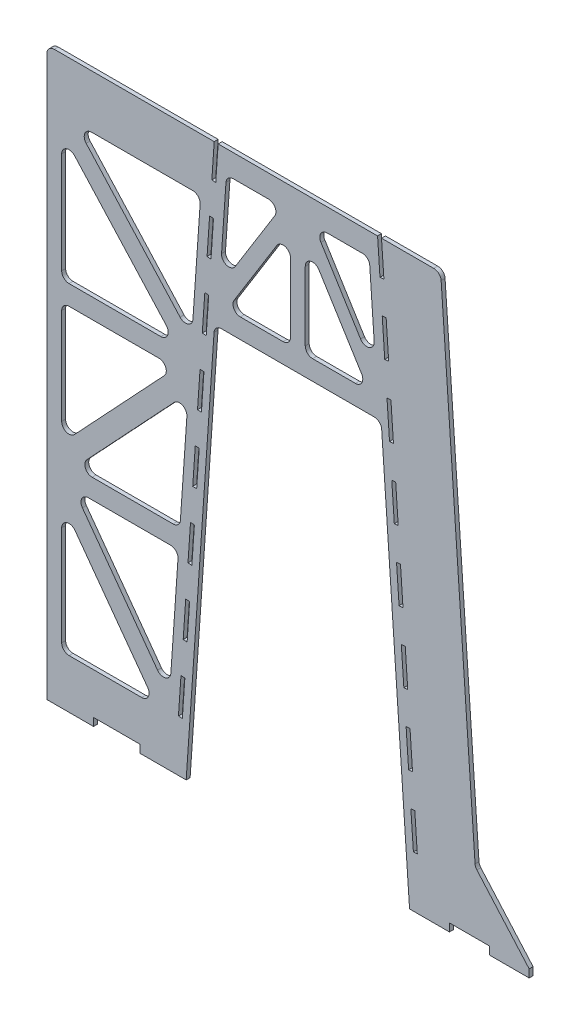
SolidWorks part; units mm, degrees
material "A-Glass Fiber"
ref_plane "Front Plane" through (0, 0, 0) normal (0, 0, 1) x (1, 0, 0)
ref_plane "Top Plane" through (0, 0, 0) normal (0, 1, 0) x (1, 0, 0)
ref_plane "Right Plane" through (0, 0, 0) normal (1, 0, 0) x (0, 0, -1)
sketch "Sketch1" plane through (0, 0, 0) normal (0, 0, 1) x (1, 0, 0)
  line L0 (-288.2759, 0) -> (288.2759, 0) construction
  line L1 (-215.8925, 1463.04) -> (215.8925, 1463.04)
  line L2 (0, 0) -> (0, 1733.4513) construction
  line L3 (19.05, 1104.9) -> (205.1391, 1104.9)
  line L4 (202.3135, 1145.5664) -> (41.4731, 1404.62)
  line L5 (205.1391, 1104.9) -> (19.05, 1404.62) construction
  line L6 (205.1391, 1104.9) -> (184.3133, 1404.62)
  line L7 (182.716, 1104.9) -> (19.05, 1368.5047)
  line L8 (19.05, 1404.62) -> (19.05, 1104.9)
  line L9 (184.3133, 1404.62) -> (19.05, 1404.62)
  line L10 (205.7153, 1463.04) -> (307.3735, 0)
  line L11 (317.5154, 0.5076) -> (215.8925, 1463.04)
  line L12 (317.5154, 0.5076) -> (317.5507, 0)
  line L13 (288.2759, 0) -> (215.0326, 1054.1)
  line L14 (447.7407, 0) -> (391.1675, 0) construction
  line L15 (266.6925, 1463.04) -> (368.5375, 1463.04)
  line L16 (368.5375, 1463.04) -> (457.7693, 178.8376)
  line L81 (215.8925, 1463.04) -> (266.6925, 1463.04)
  line L82 (-215.8925, 1463.04) -> (-647.7182, 1463.04)
  line L88 (317.5507, 0) -> (307.3718, 0)
  line L90 (215.0326, 1054.1) -> (-215.0326, 1054.1)
  line L92 (307.3718, 0) -> (288.2759, 0)
  line L93 (-288.2759, 0) -> (-215.0326, 1054.1)
  line L94 (-307.3735, 0) -> (-288.2759, 0)
  line L97 (-317.5507, 0) -> (-307.3735, 0)
  line L98 (-317.5154, 0.5076) -> (-317.5507, 0)
  line L99 (-317.5154, 0.5076) -> (-215.8925, 1463.04)
  line L100 (-205.7153, 1463.04) -> (-307.3735, 0)
  line L124 (-184.3133, 1404.62) -> (-19.05, 1404.62)
  line L125 (-19.05, 1404.62) -> (-19.05, 1104.9)
  line L126 (-182.716, 1104.9) -> (-19.05, 1368.5047)
  line L127 (-205.1391, 1104.9) -> (-19.05, 1404.62) construction
  line L128 (-202.3135, 1145.5664) -> (-41.4731, 1404.62)
  line L129 (-205.1391, 1104.9) -> (-184.3133, 1404.62)
  line L130 (-19.05, 1104.9) -> (-205.1391, 1104.9)
  line L131 (-317.5507, 0) -> (-647.7182, 0)
  line L132 (-647.7182, 0) -> (-647.7182, 1463.04)
  line L133 (-647.7182, 0) -> (-317.5507, 0)
  line L134 (-308.7262, 127) -> (-647.7182, 127)
  line L135 (-647.7182, 1325.88) -> (-225.423, 1325.88)
  line L136 (317.5507, 0) -> (368.3507, 0)
  line L137 (368.3507, 0) -> (266.6925, 1463.04)
  line L138 (368.3507, 0) -> (317.5507, 0)
  line L139 (-250.8842, 1325.88) -> (-334.1875, 127)
  line L140 (-609.6182, 127) -> (-609.6182, 1325.88)
  line L141 (-306.1844, 530.0133) -> (-609.6182, 530.0133)
  line L142 (-278.1813, 933.0267) -> (-609.6182, 933.0267)
  line L143 (-304.4195, 555.4133) -> (-609.6182, 555.4133)
  line L144 (-307.9493, 504.6133) -> (-609.6182, 504.6133)
  line L145 (-279.9462, 907.6267) -> (-609.6182, 907.6267)
  line L146 (-276.4164, 958.4267) -> (-609.6182, 958.4267)
  line L147 (-334.1875, 127) -> (-609.6182, 504.6133) construction
  line L148 (-609.6182, 555.4133) -> (-279.9462, 907.6267) construction
  line L149 (-276.4164, 958.4267) -> (-609.6182, 1325.88) construction
  line L150 (-331.453, 166.3535) -> (-578.1794, 504.6133)
  line L151 (-574.8276, 555.4133) -> (-282.736, 867.4768)
  line L152 (-273.976, 993.5478) -> (-575.3304, 1325.88)
  line L153 (-365.6263, 127) -> (-609.6182, 461.511)
  line L154 (-609.6182, 592.5827) -> (-314.7368, 907.6267)
  line L155 (-310.7042, 958.4267) -> (-609.6182, 1288.0676)
  line L156 (368.3507, 0) -> (596.9507, 0)
  line L157 (596.9507, 0) -> (596.9507, 20.32)
  line L158 (596.9507, 20.32) -> (347.1719, 304.8)
  point P0 (0, 0)
  point P3 (0, 0)
  point P106 (0, 0)
  point P118 (0, 1054.1)
  dimension "D6" = 25.4
  dimension "D7" = 50.8
  dimension "D8" = 58.42
  dimension "D9" = 19.05
  dimension "D10" = 647.7182
  dimension "D11" = 10.1527
  dimension "D12" = 25.4
  dimension "D13" = 25.4
  dimension "D14" = 25.4
  dimension "D15" = 25.4
  dimension "D16" = 25.4
  dimension "D17" = 25.4
  dimension "D18" = 1463.04
  dimension "D19" = 288.2759
  dimension "D20" = 29.2044
  dimension "D21" = 101.6
  dimension "D22" = 19.05
  dimension "D23" = 19.05
  dimension "D24" = 1054.1
  dimension "D25" = 20.32
  dimension "D37" = 127
  dimension "D38" = 50.8
  dimension "D39" = 25.4
  dimension "D40" = 38.1
  dimension "D41" = 403.0133
  dimension "D42" = 403.0133
  dimension "D43" = 25.4
  dimension "D44" = 25.4
  dimension "D45" = 25.4
  dimension "D46" = 25.4
  dimension "D47" = 279.4
  dimension "D48" = 304.8
  dimension "D49" = 50.8
  dimension "D52" = 137.16
extrude "Boss-Extrude1" add sketch "Sketch1" along normal blind 10.16
fillet "Fillet1" radius 19.05 35 edges at (-215.0326, 1054.1, 5.08) (215.0326, 1054.1, 5.08) (-202.3135, 1145.5664, 5.08) (-19.05, 1104.9, 5.08) (-182.716, 1104.9, 5.08) (-19.05, 1368.5047, 5.08) (-41.4731, 1404.62, 5.08) (-184.3133, 1404.62, 5.08) (-647.7182, 1463.04, 5.08) (-250.8842, 1325.88, 5.08) (-575.3304, 1325.88, 5.08) (-273.976, 993.5478, 5.08) (-609.6182, 958.4267, 5.08) (-609.6182, 1288.0676, 5.08) (-310.7042, 958.4267, 5.08) (-609.6182, 592.5827, 5.08) (-314.7368, 907.6267, 5.08) (-609.6182, 907.6267, 5.08) (-574.8276, 555.4133, 5.08) (-304.4195, 555.4133, 5.08) (-282.736, 867.4768, 5.08) (-307.9493, 504.6133, 5.08) (-331.453, 166.3535, 5.08) (-578.1794, 504.6133, 5.08) (-609.6182, 461.511, 5.08) (-365.6263, 127, 5.08) (-609.6182, 127, 5.08) (19.05, 1104.9, 5.08) (184.3133, 1404.62, 5.08) (41.4731, 1404.62, 5.08) (182.716, 1104.9, 5.08) (19.05, 1368.5047, 5.08) (202.3135, 1145.5664, 5.08) (457.7693, 178.8376, 5.08) (368.5375, 1463.04, 5.08)
sketch "Sketch2" plane through (0, 0, 10.16) normal (0, 0, 1) x (1, 0, 0)
  line L28 (215.8818, 1463.04) -> (205.7153, 1463.04) construction
  line L29 (205.7153, 1463.04) -> (211.9231, 1373.6642) construction
  line L30 (211.9231, 1373.6642) -> (222.0407, 1374.3669) construction
  line L31 (222.0407, 1374.3669) -> (215.8818, 1463.04) construction
  line L32 (217.7192, 1290.2141) -> (224.241, 1196.3181) construction
  line L33 (224.241, 1196.3181) -> (234.3587, 1197.0208) construction
  line L34 (234.3587, 1197.0208) -> (227.8369, 1290.9169) construction
  line L35 (227.8369, 1290.9169) -> (217.7192, 1290.2141) construction
  line L64 (230.039, 1112.8414) -> (236.5589, 1018.9719) construction
  line L65 (236.5589, 1018.9719) -> (246.6766, 1019.6747) construction
  line L66 (246.6766, 1019.6747) -> (240.1567, 1113.5442) construction
  line L67 (240.1567, 1113.5442) -> (230.039, 1112.8414) construction
  line L68 (242.3588, 935.4688) -> (248.8768, 841.6258) construction
  line L69 (248.8768, 841.6258) -> (258.9945, 842.3285) construction
  line L70 (258.9945, 842.3285) -> (252.4764, 936.1715) construction
  line L71 (252.4764, 936.1715) -> (242.3588, 935.4688) construction
  line L72 (254.6785, 758.0961) -> (261.1947, 664.2796) construction
  line L73 (261.1947, 664.2796) -> (271.3124, 664.9824) construction
  line L74 (271.3124, 664.9824) -> (264.7962, 758.7989) construction
  line L75 (264.7962, 758.7989) -> (254.6785, 758.0961) construction
  line L76 (266.9983, 580.7234) -> (273.5126, 486.9335) construction
  line L77 (273.5126, 486.9335) -> (283.6303, 487.6362) construction
  line L78 (283.6303, 487.6362) -> (277.1159, 581.4262) construction
  line L79 (277.1159, 581.4262) -> (266.9983, 580.7234) construction
  line L80 (279.318, 403.3508) -> (285.8305, 309.5874) construction
  line L81 (285.8305, 309.5874) -> (295.9482, 310.2901) construction
  line L82 (295.9482, 310.2901) -> (289.4357, 404.0535) construction
  line L83 (289.4357, 404.0535) -> (279.318, 403.3508) construction
  line L84 (291.6378, 225.9781) -> (298.1484, 132.2412) construction
  line L85 (298.1484, 132.2412) -> (308.2661, 132.944) construction
  line L86 (308.2661, 132.944) -> (301.7555, 226.6808) construction
  line L87 (301.7555, 226.6808) -> (291.6378, 225.9781) construction
  line L116 (215.8818, 1463.04) -> (205.7153, 1463.04)
  line L117 (205.7153, 1463.04) -> (211.9231, 1373.6642)
  line L118 (211.9231, 1373.6642) -> (222.0407, 1374.3669)
  line L119 (222.0407, 1374.3669) -> (215.8818, 1463.04)
  line L120 (217.7192, 1290.2141) -> (224.241, 1196.3181)
  line L121 (224.241, 1196.3181) -> (234.3587, 1197.0208)
  line L122 (234.3587, 1197.0208) -> (227.8369, 1290.9169)
  line L123 (227.8369, 1290.9169) -> (217.7192, 1290.2141)
  line L152 (230.039, 1112.8414) -> (236.5589, 1018.9719)
  line L153 (236.5589, 1018.9719) -> (246.6766, 1019.6747)
  line L154 (246.6766, 1019.6747) -> (240.1567, 1113.5442)
  line L155 (240.1567, 1113.5442) -> (230.039, 1112.8414)
  line L156 (242.3588, 935.4688) -> (248.8768, 841.6258)
  line L157 (248.8768, 841.6258) -> (258.9945, 842.3285)
  line L158 (258.9945, 842.3285) -> (252.4764, 936.1715)
  line L159 (252.4764, 936.1715) -> (242.3588, 935.4688)
  line L160 (254.6785, 758.0961) -> (261.1947, 664.2796)
  line L161 (261.1947, 664.2796) -> (271.3124, 664.9824)
  line L162 (271.3124, 664.9824) -> (264.7962, 758.7989)
  line L163 (264.7962, 758.7989) -> (254.6785, 758.0961)
  line L164 (266.9983, 580.7234) -> (273.5126, 486.9335)
  line L165 (273.5126, 486.9335) -> (283.6303, 487.6362)
  line L166 (283.6303, 487.6362) -> (277.1159, 581.4262)
  line L167 (277.1159, 581.4262) -> (266.9983, 580.7234)
  line L168 (279.318, 403.3508) -> (285.8305, 309.5874)
  line L169 (285.8305, 309.5874) -> (295.9482, 310.2901)
  line L170 (295.9482, 310.2901) -> (289.4357, 404.0535)
  line L171 (289.4357, 404.0535) -> (279.318, 403.3508)
  line L172 (291.6378, 225.9781) -> (298.1484, 132.2412)
  line L173 (298.1484, 132.2412) -> (308.2661, 132.944)
  line L174 (308.2661, 132.944) -> (301.7555, 226.6808)
  line L175 (301.7555, 226.6808) -> (291.6378, 225.9781)
  line L194 (-134.539, 20.32) -> (-288.2759, 20.32) construction
  line L195 (-647.7182, 0) -> (-527.4335, 0)
  line L196 (-647.7182, 0) -> (-647.7182, 20.32)
  line L197 (-647.7182, 20.32) -> (-527.4335, 20.32)
  line L198 (-527.4335, 0) -> (-527.4335, 20.32)
  line L199 (-288.2759, 0) -> (-216.2645, 1036.3705) construction
  line L200 (-527.4335, 0) -> (-407.1487, 0)
  line L201 (-527.4335, 0) -> (-527.4335, 20.32)
  line L202 (-527.4335, 20.32) -> (-407.1487, 20.32)
  line L203 (-407.1487, 0) -> (-407.1487, 20.32)
  line L204 (-407.1487, 0) -> (-286.864, 0)
  line L205 (-407.1487, 0) -> (-407.1487, 20.32)
  line L206 (-407.1487, 20.32) -> (-286.864, 20.32)
  line L207 (-286.864, 0) -> (-286.864, 20.32)
  line L213 (288.2759, 20.32) -> (134.539, 20.32) construction
  line L230 (288.2759, 0) -> (391.1675, 0)
  line L231 (288.2759, 0) -> (288.2759, 20.32)
  line L232 (288.2759, 20.32) -> (391.1675, 20.32)
  line L233 (391.1675, 0) -> (391.1675, 20.32)
  line L235 (391.1675, 0) -> (494.0591, 0)
  line L236 (391.1675, 0) -> (391.1675, 20.32)
  line L237 (391.1675, 20.32) -> (494.0591, 20.32)
  line L238 (494.0591, 0) -> (494.0591, 20.32)
  line L239 (494.0591, 0) -> (596.9507, 0)
  line L240 (494.0591, 0) -> (494.0591, 20.32)
  line L241 (494.0591, 20.32) -> (596.9507, 20.32)
  line L242 (596.9507, 0) -> (596.9507, 20.32)
  line L254 (-205.7153, 1463.04) -> (-215.8818, 1463.04) construction
  line L255 (-215.8818, 1463.04) -> (-222.0407, 1374.3669) construction
  line L256 (-222.0407, 1374.3669) -> (-211.9231, 1373.6642) construction
  line L257 (-211.9231, 1373.6642) -> (-205.7153, 1463.04) construction
  line L258 (-224.241, 1196.3181) -> (-217.7192, 1290.2141) construction
  line L259 (-217.7192, 1290.2141) -> (-227.8369, 1290.9169) construction
  line L260 (-227.8369, 1290.9169) -> (-234.3587, 1197.0208) construction
  line L261 (-234.3587, 1197.0208) -> (-224.241, 1196.3181) construction
  line L262 (-236.5589, 1018.9719) -> (-230.039, 1112.8414) construction
  line L263 (-230.039, 1112.8414) -> (-240.1567, 1113.5442) construction
  line L264 (-240.1567, 1113.5442) -> (-246.6766, 1019.6747) construction
  line L265 (-246.6766, 1019.6747) -> (-236.5589, 1018.9719) construction
  line L266 (-248.8768, 841.6258) -> (-242.3588, 935.4688) construction
  line L267 (-242.3588, 935.4688) -> (-252.4764, 936.1715) construction
  line L268 (-252.4764, 936.1715) -> (-258.9945, 842.3285) construction
  line L269 (-258.9945, 842.3285) -> (-248.8768, 841.6258) construction
  line L270 (-261.1947, 664.2796) -> (-254.6785, 758.0961) construction
  line L271 (-254.6785, 758.0961) -> (-264.7962, 758.7989) construction
  line L272 (-264.7962, 758.7989) -> (-271.3124, 664.9824) construction
  line L273 (-271.3124, 664.9824) -> (-261.1947, 664.2796) construction
  line L274 (-273.5126, 486.9335) -> (-266.9983, 580.7234) construction
  line L275 (-266.9983, 580.7234) -> (-277.1159, 581.4262) construction
  line L276 (-277.1159, 581.4262) -> (-283.6303, 487.6362) construction
  line L277 (-283.6303, 487.6362) -> (-273.5126, 486.9335) construction
  line L278 (-285.8305, 309.5874) -> (-279.318, 403.3508) construction
  line L279 (-279.318, 403.3508) -> (-289.4357, 404.0535) construction
  line L280 (-289.4357, 404.0535) -> (-295.9482, 310.2901) construction
  line L281 (-295.9482, 310.2901) -> (-285.8305, 309.5874) construction
  line L282 (-298.1484, 132.2412) -> (-291.6378, 225.9781) construction
  line L283 (-291.6378, 225.9781) -> (-301.7555, 226.6808) construction
  line L284 (-301.7555, 226.6808) -> (-308.2661, 132.944) construction
  line L285 (-308.2661, 132.944) -> (-298.1484, 132.2412) construction
  line L298 (-205.7153, 1463.04) -> (-215.8818, 1463.04)
  line L299 (-215.8818, 1463.04) -> (-222.0407, 1374.3669)
  line L300 (-222.0407, 1374.3669) -> (-211.9231, 1373.6642)
  line L301 (-211.9231, 1373.6642) -> (-205.7153, 1463.04)
  line L302 (-224.241, 1196.3181) -> (-217.7192, 1290.2141)
  line L303 (-217.7192, 1290.2141) -> (-227.8369, 1290.9169)
  line L304 (-227.8369, 1290.9169) -> (-234.3587, 1197.0208)
  line L305 (-234.3587, 1197.0208) -> (-224.241, 1196.3181)
  line L306 (-236.5589, 1018.9719) -> (-230.039, 1112.8414)
  line L307 (-230.039, 1112.8414) -> (-240.1567, 1113.5442)
  line L308 (-240.1567, 1113.5442) -> (-246.6766, 1019.6747)
  line L309 (-246.6766, 1019.6747) -> (-236.5589, 1018.9719)
  line L310 (-248.8768, 841.6258) -> (-242.3588, 935.4688)
  line L311 (-242.3588, 935.4688) -> (-252.4764, 936.1715)
  line L312 (-252.4764, 936.1715) -> (-258.9945, 842.3285)
  line L313 (-258.9945, 842.3285) -> (-248.8768, 841.6258)
  line L314 (-261.1947, 664.2796) -> (-254.6785, 758.0961)
  line L315 (-254.6785, 758.0961) -> (-264.7962, 758.7989)
  line L316 (-264.7962, 758.7989) -> (-271.3124, 664.9824)
  line L317 (-271.3124, 664.9824) -> (-261.1947, 664.2796)
  line L318 (-273.5126, 486.9335) -> (-266.9983, 580.7234)
  line L319 (-266.9983, 580.7234) -> (-277.1159, 581.4262)
  line L320 (-277.1159, 581.4262) -> (-283.6303, 487.6362)
  line L321 (-283.6303, 487.6362) -> (-273.5126, 486.9335)
  line L322 (-285.8305, 309.5874) -> (-279.318, 403.3508)
  line L323 (-279.318, 403.3508) -> (-289.4357, 404.0535)
  line L324 (-289.4357, 404.0535) -> (-295.9482, 310.2901)
  line L325 (-295.9482, 310.2901) -> (-285.8305, 309.5874)
  line L326 (-298.1484, 132.2412) -> (-291.6378, 225.9781)
  line L327 (-291.6378, 225.9781) -> (-301.7555, 226.6808)
  line L328 (-301.7555, 226.6808) -> (-308.2661, 132.944)
  line L329 (-308.2661, 132.944) -> (-298.1484, 132.2412)
extrude "Cut-Extrude1" cut sketch "Sketch2" against normal blind 12.7 contours L200 L203 L202 L198 | L235 L238 L237 L233 | L118 L119 L116 L117 | L122 L123 L120 L121 | L154 L155 L152 L153 | L158 L159 L156 L157 | L162 L163 L160 L161 | L166 L167 L164 L165 | L170 L171 L168 L169 | L174 L175 L172 L173 | L328 L329 L326 L327 | L324 L325 L322 L323 | L320 L321 L318 L319 | L316 L317 L314 L315 | L312 L313 L310 L311 | L308 L309 L306 L307 | L304 L305 L302 L303 | L300 L301 L298 L299
sketch "Sketch4" [suppressed] plane through (0, 0, 10.16) normal (0, 0, 1) x (1, 0, 0)
  line L0 (596.9507, 0) -> (494.0591, 0) construction
  line L1 (596.9507, 0) -> (596.9507, 20.32) construction
  line L2 (596.9507, 0) -> (494.0591, 0)
  line L3 (596.9507, 0) -> (596.9507, 20.32)
  line L4 (337.4418, 445.6368) -> (336.7375, 455.7724)
  line L5 (337.4418, 445.6368) -> (286.7919, 442.1174)
  line L6 (336.7375, 455.7724) -> (286.0876, 452.253)
  line L7 (286.7919, 442.1174) -> (286.0876, 452.253)
  line L8 (388.0923, 449.1521) -> (387.388, 459.2876)
  line L9 (388.0923, 449.1521) -> (438.7422, 452.6714)
  line L10 (387.388, 459.2876) -> (438.0379, 462.807)
  line L11 (438.7422, 452.6714) -> (438.0379, 462.807)
  line L12 (369.7694, 1445.3105) -> (457.3235, 185.2533) construction
  point P2 (596.9507, 0)
